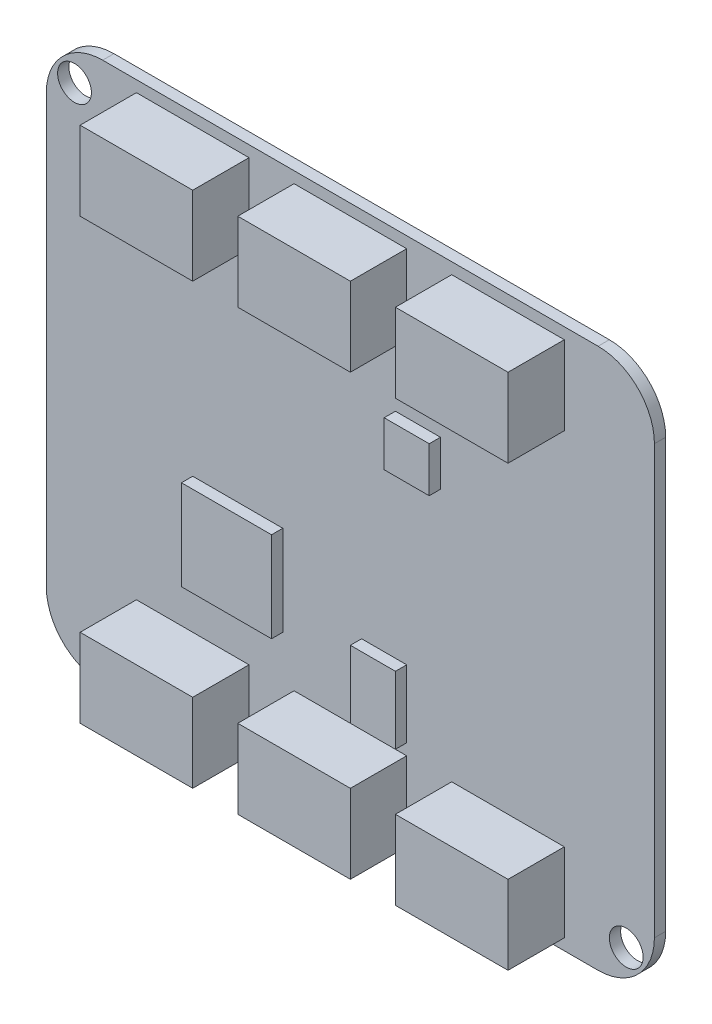
SolidWorks part; units mm, degrees
ref_plane "正面" through (0, 0, 0) normal (0, 0, 1) x (1, 0, 0)
ref_plane "平面" through (0, 0, 0) normal (0, 1, 0) x (1, 0, 0)
ref_plane "右側面" through (0, 0, 0) normal (1, 0, 0) x (0, 0, -1)
sketch "ｽｹｯﾁ1" plane through (0, 0, 0) normal (0, 0, 1) x (1, 0, 0)
  line L1 (-27, -24) -> (27, -24)
  line L2 (-27, -24) -> (-27, 24)
  line L3 (-27, 24) -> (27, 24)
  line L4 (27, -24) -> (27, 24)
  line L5 (-27, -24) -> (27, 24) construction
  line L6 (-27, 24) -> (27, -24) construction
  point P0 (0, 0)
  dimension "D1" = 48
  dimension "D2" = 54
extrude "ﾎﾞｽ - 押し出し1" add sketch "ｽｹｯﾁ1" along normal blind 1
sketch "ｽｹｯﾁ2" plane through (0, 0, 1) normal (0, 0, 1) x (1, 0, 0)
  line L1 (-24.5, -21) -> (24.5, -21) construction
  line L2 (-24.5, -21) -> (-24.5, 21) construction
  line L3 (-24.5, 21) -> (24.5, 21) construction
  line L4 (24.5, -21) -> (24.5, 21) construction
  line L5 (-24.5, -21) -> (24.5, 21) construction
  line L6 (-24.5, 21) -> (24.5, -21) construction
  circle A0 centre (-24.5, 21) radius 1.5
  circle A1 centre (24.5, -21) radius 1.5
  point P0 (0, 0)
  dimension "D3" = 3
  dimension "D4" = 3
  dimension "D1" = 49
  dimension "D2" = 42
extrude "ｶｯﾄ - 押し出し1" cut sketch "ｽｹｯﾁ2" against normal through all
fillet "ﾌｨﾚｯﾄ1" radius 5 4 edges at (27, 24, 0.5) (27, -24, 0.5) (-27, -24, 0.5) (-27, 24, 0.5)
sketch "ｽｹｯﾁ3" plane through (0, 0, 1) normal (0, 0, 1) x (1, 0, 0)
  line L0 (27, -19) -> (27, 19) construction
  line L1 (-19, 23) -> (-9, 23)
  line L2 (-19, 23) -> (-19, 16)
  line L3 (-19, 16) -> (-9, 16)
  line L4 (-9, 23) -> (-9, 16)
  line L5 (-5, 23) -> (5, 23)
  line L6 (-5, 23) -> (-5, 16)
  line L7 (-5, 16) -> (5, 16)
  line L8 (5, 23) -> (5, 16)
  line L9 (9, 23) -> (19, 23)
  line L10 (9, 23) -> (9, 16)
  line L11 (9, 16) -> (19, 16)
  line L12 (19, 23) -> (19, 16)
  line L13 (22, 24) -> (-22, 24) construction
  line L14 (-22, -24) -> (22, -24) construction
  line L15 (-19, -16) -> (-9, -16)
  line L16 (-19, -16) -> (-19, -23)
  line L17 (-19, -23) -> (-9, -23)
  line L18 (-9, -16) -> (-9, -23)
  line L19 (-5, -16) -> (5, -16)
  line L20 (-5, -16) -> (-5, -23)
  line L21 (-5, -23) -> (5, -23)
  line L22 (5, -16) -> (5, -23)
  line L23 (9, -16) -> (19, -16)
  line L24 (9, -16) -> (9, -23)
  line L25 (9, -23) -> (19, -23)
  line L26 (19, -16) -> (19, -23)
  dimension "D1" = 8
  dimension "D2" = 10
  dimension "D3" = 7
  dimension "D4" = 10
  dimension "D5" = 7
  dimension "D6" = 10
  dimension "D7" = 7
  dimension "D8" = 1
  dimension "D9" = 1
  dimension "D10" = 1
  dimension "D11" = 4
  dimension "D12" = 4
  dimension "D13" = 1
  dimension "D14" = 8
  dimension "D15" = 10
  dimension "D16" = 7
  dimension "D17" = 4
  dimension "D18" = 1
  dimension "D19" = 10
  dimension "D20" = 7
  dimension "D21" = 4
  dimension "D22" = 1
  dimension "D23" = 10
  dimension "D24" = 7
extrude "ﾎﾞｽ - 押し出し2" add sketch "ｽｹｯﾁ3" along normal blind 5
sketch "ｽｹｯﾁ4" plane through (0, 0, 1) normal (0, 0, 1) x (1, 0, 0)
  line L0 (-27, 19) -> (-27, -19) construction
  line L1 (-14, -4) -> (-6, -4)
  line L2 (-14, -4) -> (-14, -12)
  line L3 (-14, -12) -> (-6, -12)
  line L4 (-6, -4) -> (-6, -12)
  line L5 (-9, -16) -> (-19, -16) construction
  line L6 (9, -16) -> (9, -23) construction
  line L7 (1, -9) -> (5, -9)
  line L8 (1, -9) -> (1, -15)
  line L9 (1, -15) -> (5, -15)
  line L10 (5, -9) -> (5, -15)
  line L11 (5, -16) -> (-5, -16) construction
  line L12 (-5, 16) -> (5, 16) construction
  line L13 (4, 10) -> (8, 10)
  line L14 (4, 10) -> (4, 6)
  line L15 (4, 6) -> (8, 6)
  line L16 (8, 10) -> (8, 6)
  line L17 (5, 16) -> (5, 23) construction
  dimension "D1" = 8
  dimension "D2" = 8
  dimension "D3" = 13
  dimension "D4" = 4
  dimension "D5" = 7
  dimension "D6" = 4
  dimension "D7" = 1
  dimension "D8" = 6
  dimension "D9" = 4
  dimension "D10" = 4
  dimension "D11" = 6
  dimension "D12" = 1
extrude "ﾎﾞｽ - 押し出し3" add sketch "ｽｹｯﾁ4" along normal blind 1
